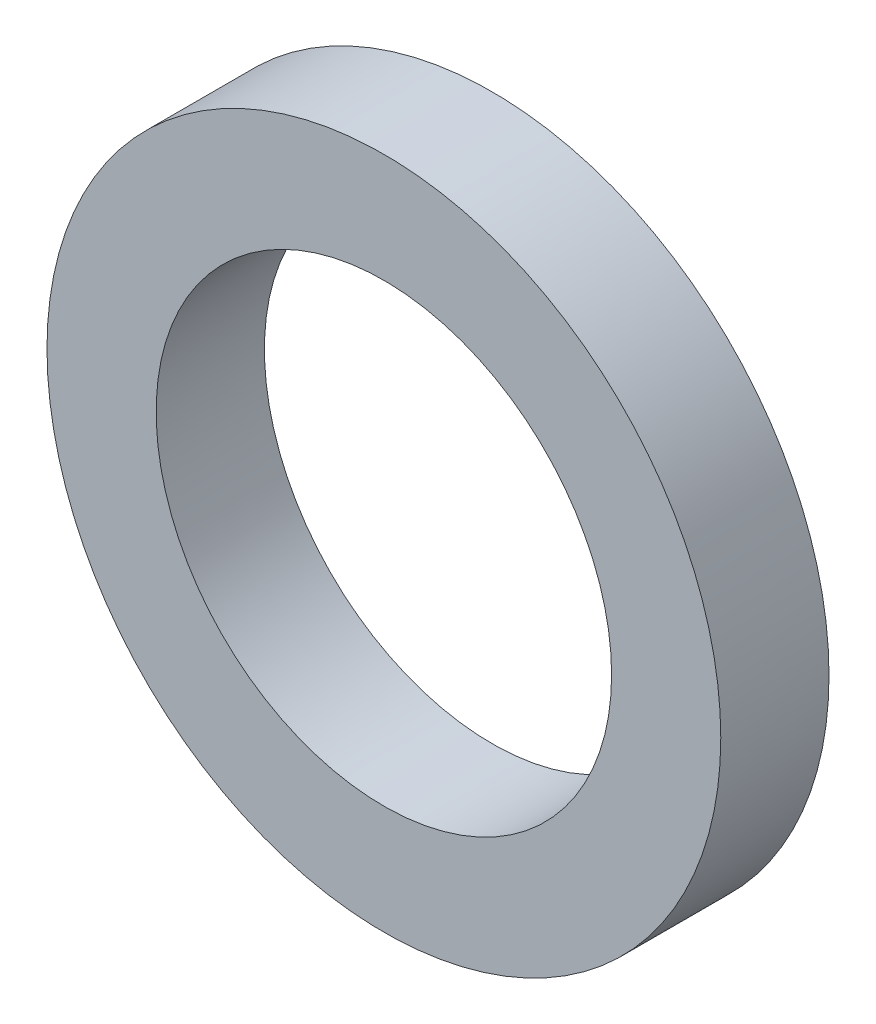
SolidWorks part; units mm, degrees
ref_plane "Front" through (0, 0, 0) normal (0, 0, 1) x (1, 0, 0)
ref_plane "Top" through (0, 0, 0) normal (0, 1, 0) x (1, 0, 0)
ref_plane "Right" through (0, 0, 0) normal (1, 0, 0) x (0, 0, -1)
sketch "Sketch1" plane through (0, 0, 0) normal (0, 0, 1) x (1, 0, 0)
  circle A0 centre (0, 0) radius 26.51
  circle A1 centre (0, 0) radius 39.22
  dimension "D1" = 78.44
  dimension "D2" = 53.02
extrude "Boss-Extrude1" add sketch "Sketch1" along normal blind 12.6
